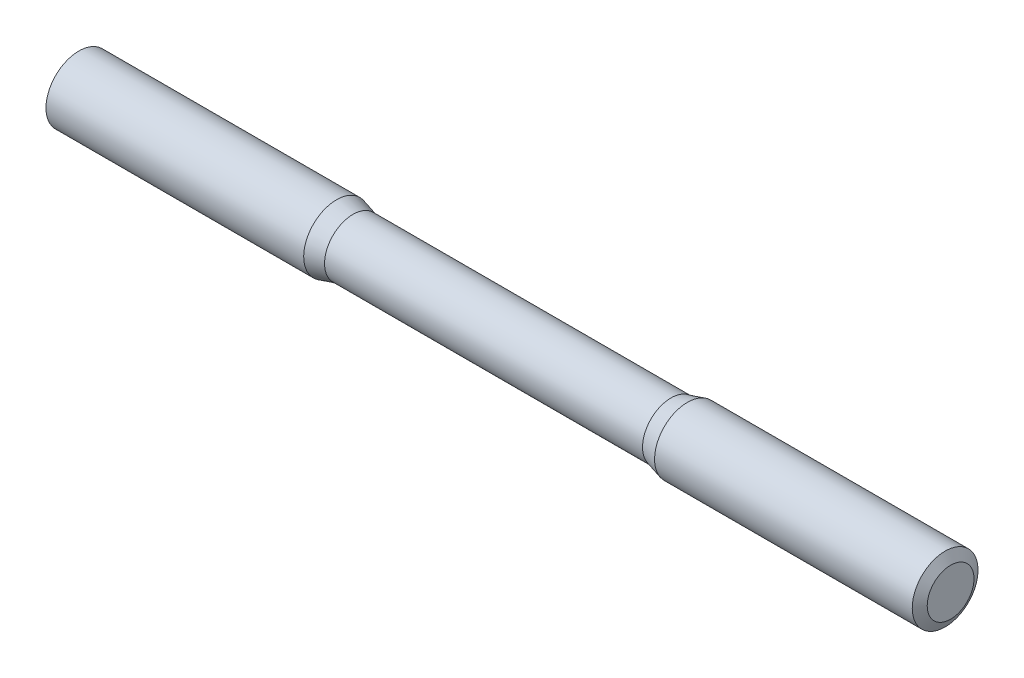
SolidWorks part; units mm, degrees
material "黄铜"
ref_plane "前视" through (0, 0, 0) normal (0, 0, 1) x (1, 0, 0)
ref_plane "上视" through (0, 0, 0) normal (0, 1, 0) x (1, 0, 0)
ref_plane "右视" through (0, 0, 0) normal (1, 0, 0) x (0, 0, -1)
sketch "尺寸草图" plane through (0, 0, 0) normal (0, 0, 1) x (1, 0, 0)
  line L0 (0, 0) -> (19.4474, 0) construction
  line L1 (-40, 0) -> (-2.7, 0) construction
  point P3 (3, 0)
  point P4 (12, 0)
  point P5 (0.75, 0)
  point P6 (-2.7, 0)
  point P7 (0, 0)
  point P8 (-0.5, 0)
  point P9 (0, 0)
  point P10 (-40, 0)
  dimension "l" = 40
  dimension "d" = 3
  dimension "b" = 12
  dimension "X" = 0.75
  dimension "ds" = 2.7
  dimension "P" = 0.5
sketch "草图1" plane through (0, 0, 0) normal (0, 0, 1) x (1, 0, 0)
  line L0 (-20, 0) -> (45.3739, 0) construction
  line L1 (-20, 1.5) -> (-8, 1.5)
  line L2 (-7.25, 1.299) -> (7.25, 1.299)
  line L3 (-20, 1.5) -> (-20, 0)
  line L4 (8, 1.5) -> (7.25, 1.299)
  line L5 (-8, 1.5) -> (-7.25, 1.299)
  line L6 (20, 0) -> (-20, 0)
  line L7 (0, 0) -> (0, -5.0983) construction
  line L8 (20, 1.5) -> (20, 0)
  line L9 (20, 1.5) -> (8, 1.5)
  point P13 (0, 1.299)
  dimension "X" = 0.75
  dimension "l/2" = 20
  dimension "b" = 12
  dimension "d/2" = 1.5
  dimension "中径" = 1.299
revolve "基体-旋转" add sketch "草图1" angle 360 about L0
cosmetic thread "装饰螺纹线1" parameters "D1"=12, "D2"=2.7778
cosmetic thread "装饰螺纹线2" parameters "D1"=12, "D2"=2.7778
sketch "草图2" plane through (0, 0, 0) normal (0, 0, 1) x (1, 0, 0)
  line L0 (-20.25, 1.5) -> (-19.75, 1.5)
  line L1 (-19.75, 1.5) -> (-20, 1.067)
  line L2 (-20, 1.067) -> (-20.25, 1.5)
  line L3 (-8, 1.5) -> (-20, 1.5) construction
  line L4 (-20, 1.5) -> (-20, -1.5) construction
  line L5 (-26.9524, 0) -> (-19.4497, 0) construction
  line L6 (-20, 0) -> (45.3739, 0) construction
  dimension "D1" = 60
  dimension "D2" = 60
  dimension "D3" = 0.433
revolve "螺纹切除" cut sketch "草图2" angle 360 about L5
pattern_linear "左螺纹阵列" [suppressed] count 25 spacing 0.5
mirror "镜向1" about plane through (0, 0, 0) normal (1, 0, 0) of "螺纹切除"
mirror "镜向2" [suppressed] about plane through (0, 0, 0) normal (1, 0, 0)
